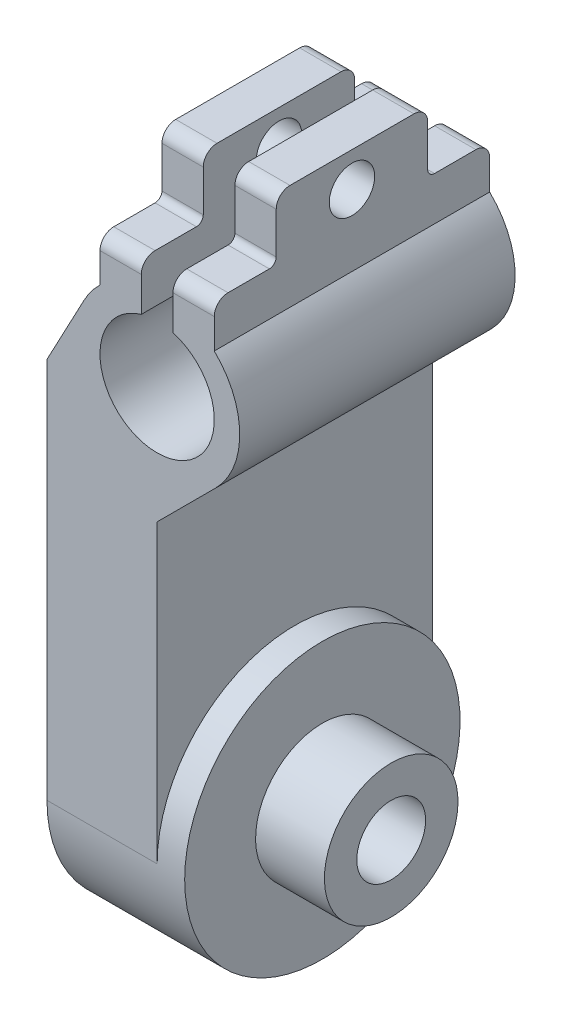
SolidWorks part; units mm, degrees
ref_plane "前视基准面" through (0, 0, 0) normal (0, 0, 1) x (1, 0, 0)
ref_plane "上视基准面" through (0, 0, 0) normal (0, 1, 0) x (1, 0, 0)
ref_plane "右视基准面" through (0, 0, 0) normal (1, 0, 0) x (0, 0, -1)
other "Configuration Table"
sketch "草图1" plane through (0, 0, 0) normal (0, 0, 1) x (1, 0, 0)
  line L0 (-1.15, 3.9875) -> (-1.15, 12)
  line L1 (0, 0) -> (0, 9.969) construction
  line L2 (-1.15, 12) -> (-4.15, 12)
  line L3 (-4.15, 12) -> (-4.15, 4.3333)
  line L4 (4.15, 12) -> (4.15, 4.3333)
  line L5 (1.15, 12) -> (4.15, 12)
  line L6 (1.15, 3.9875) -> (1.15, 12)
  line L7 (-8, -2.2655) -> (-5.2977, 2.8168)
  line L8 (-8, -2.2655) -> (-8, -30)
  line L9 (4.2426, -4.2426) -> (0, -8.4853)
  line L10 (0, -8.4853) -> (0, -30)
  line L11 (-8, -30) -> (0, -30)
  arc A0 (-1.15, 3.9875) -> (1.15, 3.9875) centre (0, 0) ccw
  arc A1 (-4.15, 4.3333) -> (-5.2977, 2.8168) centre (0, 0) ccw
  arc A2 (4.2426, -4.2426) -> (4.15, 4.3333) centre (0, 0) ccw
  dimension "D1" = 8.3
  dimension "D4" = 12
  dimension "D2" = 2.3
  dimension "D3" = 12
  dimension "D5" = 3
  dimension "D6" = 30
  dimension "D7" = 152
  dimension "D8" = 8
  dimension "D9" = 135
extrude "凸台-拉伸1" add sketch "草图1" along normal mid plane 20
sketch "草图6" plane through (4.15, 0, 0) normal (1, 0, 0) x (0, 0, -1)
  line L0 (0, 0) -> (0, 16.5087) construction
  line L1 (-10, 12) -> (10, 12) construction
  line L2 (-5.5, 7.5) -> (-20.2045, 7.5)
  line L3 (-5.5, 7.5) -> (-5.5, 16.0204)
  line L4 (-5.5, 16.0204) -> (-20.2045, 16.0204)
  line L5 (-20.2045, 7.5) -> (-20.2045, 16.0204)
  line L6 (20.2045, 7.5) -> (20.2045, 16.0204)
  line L7 (5.5, 16.0204) -> (20.2045, 16.0204)
  line L8 (5.5, 7.5) -> (5.5, 16.0204)
  line L9 (5.5, 7.5) -> (20.2045, 7.5)
  circle A0 centre (0, 9.5) radius 1.65
  dimension "D3" = 3.3
  dimension "D1" = 11
  dimension "D2" = 4.5
  dimension "D4" = 2.5
extrude "切除-拉伸2" cut sketch "草图6" against normal through all
fillet "圆角1" radius 1 8 edges at (2.65, 7.5, -10) (-2.65, 7.5, -10) (-2.65, 7.5, 10) (2.65, 7.5, 10) (-2.65, 12, 5.5) (2.65, 12, -5.5) (-2.65, 12, -5.5) (2.65, 12, 5.5)
fillet "圆角2" radius 0.5 4 edges at (2.65, 7.5, -5.5) (-2.65, 7.5, -5.5) (2.65, 7.5, 5.5) (-2.65, 7.5, 5.5)
sketch "草图7" plane through (0, 0, 0) normal (1, 0, 0) x (0, 0, -1)
  line L0 (-10, -30) -> (10, -30) construction
  circle A0 centre (0, -30) radius 10
  dimension "D1" = 20
extrude "凸台-拉伸2" add sketch "草图7" against normal up to surface and the other way blind 2 up to face at (-8, -16.1327, 0)
sketch "草图8" plane through (2, 0, 0) normal (1, 0, 0) x (0, 0, -1)
  circle A0 centre (0, -30) radius 4.85
  dimension "D1" = 9.7
extrude "凸台-拉伸3" add sketch "草图8" along normal blind 5
sketch "草图9" plane through (7, 0, 0) normal (1, 0, 0) x (0, 0, -1)
  circle A0 centre (0, -30) radius 2.5
  dimension "D1" = 5
extrude "切除-拉伸3" cut sketch "草图9" against normal through all
